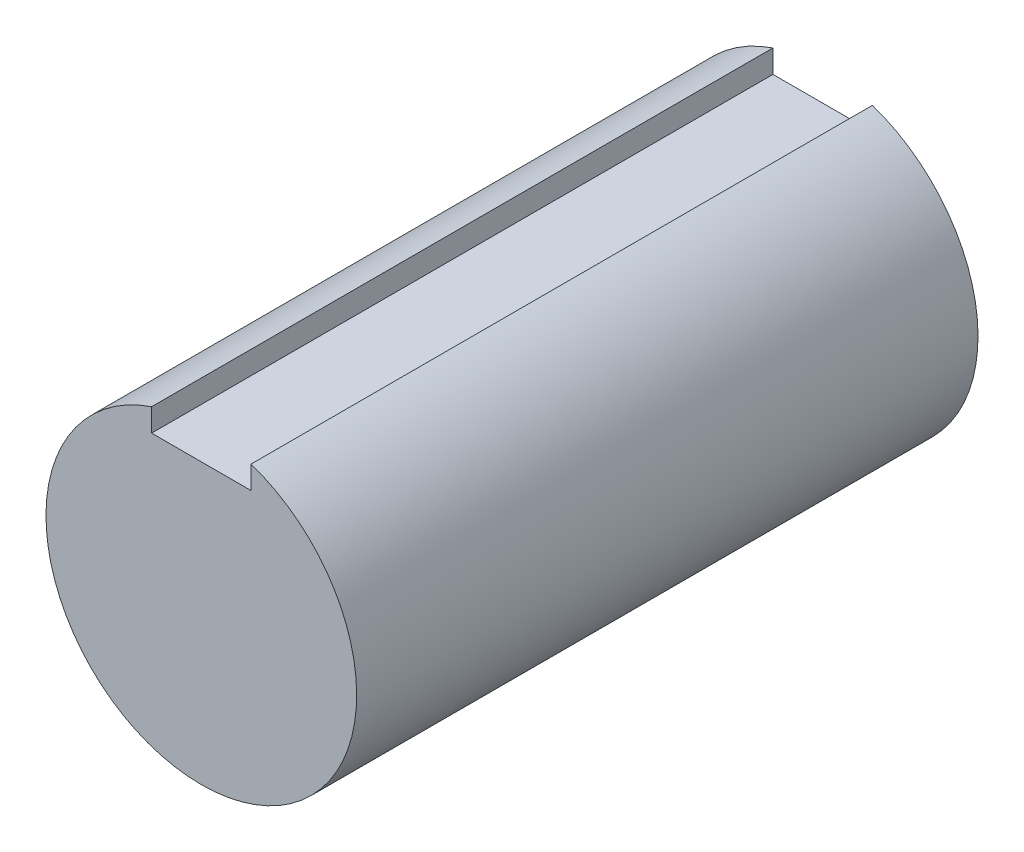
SolidWorks part; units mm, degrees
ref_plane "Front Plane" through (0, 0, 0) normal (0, 0, 1) x (1, 0, 0)
ref_plane "Top Plane" through (0, 0, 0) normal (0, 1, 0) x (1, 0, 0)
ref_plane "Right Plane" through (0, 0, 0) normal (1, 0, 0) x (0, 0, -1)
sketch "Sketch1" plane through (0, 0, 0) normal (0, 0, 1) x (1, 0, 0)
  circle A0 centre (0, 0) radius 25
extrude "Boss-Extrude2" add sketch "Sketch1" along normal blind 100
sketch "Sketch3" plane through (0, 0, 100) normal (0, 0, 1) x (1, 0, 0)
  line L0 (-8, 20) -> (8, 20)
  line L3 (-8, 20) -> (-8, 23.6854)
  line L4 (8, 20) -> (8, 23.6854)
  circle A0 centre (0, 0) radius 25
  point P8 (0, 20)
extrude "Cut-Extrude2" cut sketch "Sketch3" against normal blind 246 contours L0 L4 L3
